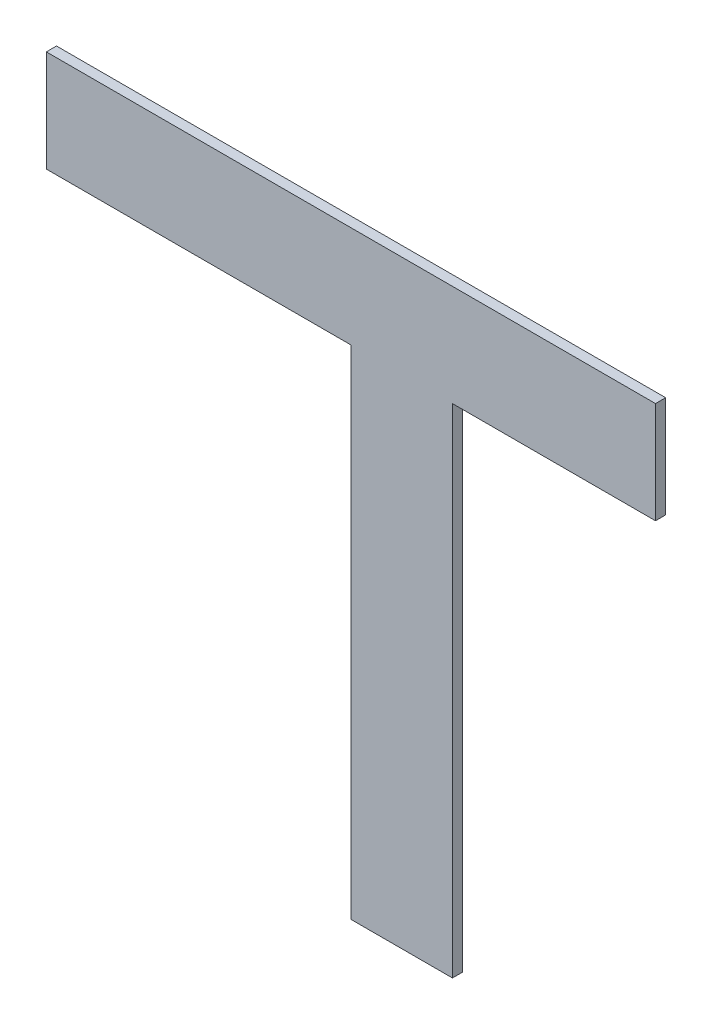
SolidWorks part; units mm, degrees
ref_plane "Front Plane" through (0, 0, 0) normal (0, 0, 1) x (1, 0, 0)
ref_plane "Top Plane" through (0, 0, 0) normal (0, 1, 0) x (1, 0, 0)
ref_plane "Right Plane" through (0, 0, 0) normal (1, 0, 0) x (0, 0, -1)
sketch "Sketch1" plane through (0, 0, 0) normal (0, 0, 1) x (1, 0, 0)
  line L0 (-101.6, 25.4) -> (50.8, 25.4)
  line L1 (50.8, 25.4) -> (50.8, 0)
  line L2 (50.8, 0) -> (-101.6, 0) construction
  line L3 (-101.6, 0) -> (-101.6, 25.4)
  line L4 (-25.4, 0) -> (-25.4, -124.46)
  line L5 (-25.4, -124.46) -> (0, -124.46)
  line L6 (0, -124.46) -> (0, 0)
  line L7 (0, 0) -> (0, -124.46)
  line L8 (-101.6, 0) -> (-25.4, 0)
  line L9 (0, 0) -> (50.8, 0)
  dimension "D1" = 152.4
  dimension "D2" = 25.4
  dimension "D3" = 25.4
  dimension "D4" = 124.46
  dimension "D5" = 50.8
extrude "Boss-Extrude1" add sketch "Sketch1" along normal mid plane 2.54 contours L6 L2 L4 L5 | L2 L9 L1 L0 L3 L8
